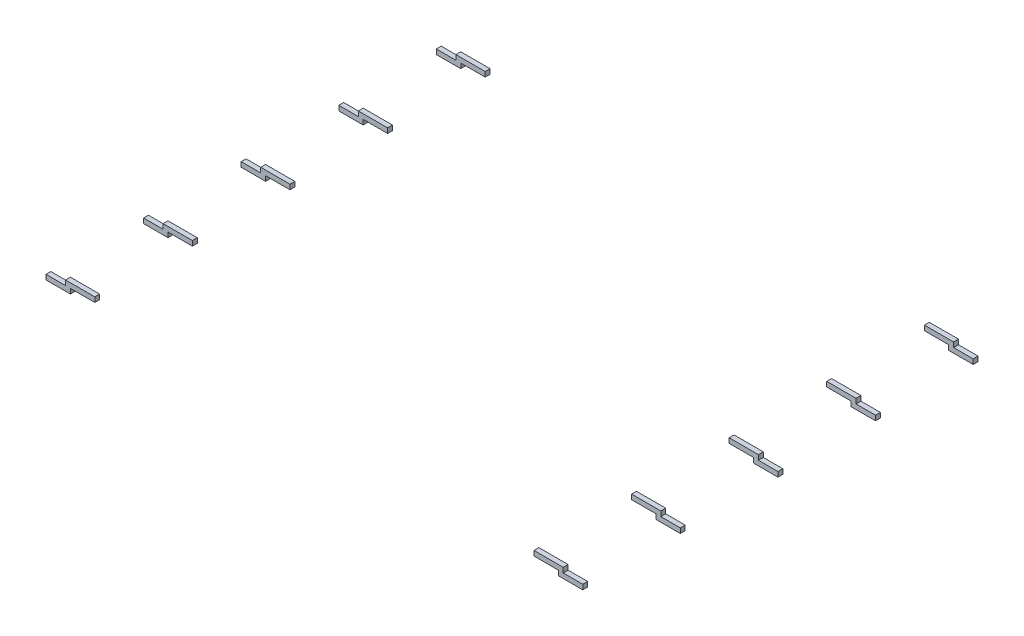
SolidWorks part; units mm, degrees
ref_plane "Front Plane" through (0, 0, 0) normal (0, 0, 1) x (1, 0, 0)
ref_plane "Top Plane" through (0, 0, 0) normal (0, 1, 0) x (1, 0, 0)
ref_plane "Right Plane" through (0, 0, 0) normal (1, 0, 0) x (0, 0, -1)
sketch "Sketch1" plane through (0, 0, 0) normal (0, 0, 1) x (1, 0, 0)
  line L0 (5.1, 0) -> (5.5, 0)
  line L1 (4.5, 0.1) -> (5.1, 0.1)
  line L2 (4.5, 0.1) -> (4.5, 0)
  line L3 (4.5, 0) -> (5, 0)
  line L4 (5.1, 0.1) -> (5.1, 0)
  line L5 (4.5, 0.1) -> (5.1, 0) construction
  line L6 (4.5, 0) -> (5.1, 0.1) construction
  line L8 (5.5, 0) -> (5.5, -0.1)
  line L9 (5.5, -0.1) -> (5, -0.1)
  line L10 (5, 0) -> (5, -0.1)
  line L11 (5.5, 0) -> (5, -0.1) construction
  line L12 (5.5, -0.1) -> (5, 0) construction
  line L13 (0, -1000) -> (0, 49000) construction
  line L14 (-5.5, -0.1) -> (-5, 0) construction
  line L15 (-5.5, 0) -> (-5, -0.1) construction
  line L16 (-4.5, 0) -> (-5.1, 0.1) construction
  line L17 (-4.5, 0.1) -> (-5.1, 0) construction
  line L34 (-5, 0) -> (-5, -0.1)
  line L35 (-5.5, -0.1) -> (-5, -0.1)
  line L36 (-5.5, 0) -> (-5.5, -0.1)
  line L37 (-5.1, 0.1) -> (-5.1, 0)
  line L38 (-4.5, 0) -> (-5, 0)
  line L39 (-4.5, 0.1) -> (-4.5, 0)
  line L40 (-4.5, 0.1) -> (-5.1, 0.1)
  line L41 (-5.1, 0) -> (-5.5, 0)
  point P0 (4.8, 0.05)
  point P5 (5.25, -0.05)
  point P10 (-4.6431, 0.025)
  point P11 (5, -0.05)
  point P13 (-3.9619, 0.075)
  point P16 (-2.5332, 0.075)
  point P17 (-0.8417, 0.075)
  point P18 (0.7237, 0.025)
  point P19 (0.978, 0.075)
  point P28 (-5.25, -0.05)
  point P29 (-4.8, 0.05)
  point P30 (5.25, 0.2103)
  point P31 (5.25, -0.2762)
  dimension "D1" = 0.1
  dimension "D2" = 0.6
  dimension "D3" = 0.5
  dimension "D4" = 0.5
  dimension "D5" = 10
extrude "Boss-Extrude1" add sketch "Sketch1" along normal mid plane 0.1
pattern_linear "LPattern1" count 5 spacing 2 along (0, 0, 1) of "Boss-Extrude1"
sketch "Sketch2" plane through (0, 0, 0) normal (0, 1, 0) x (1, 0, 0)
  line L1 (-4.8, 0.8) -> (4.8, 0.8)
  line L2 (-4.8, 0.8) -> (-4.8, -8.8)
  line L3 (-4.8, -8.8) -> (4.8, -8.8)
  line L4 (4.8, 0.8) -> (4.8, -8.8)
  line L5 (-4.8, 0.8) -> (4.8, -8.8) construction
  line L6 (-4.8, -8.8) -> (4.8, 0.8) construction
  point P0 (0, -4)
  point P5 (0.3134, 4.8742)
  point P6 (0, 0)
  point P7 (0, 0)
  point P8 (0.5034, 4.9)
  point P9 (0, 0)
  point P10 (0, 0)
  point P12 (0, 0)
  point P13 (0, 3.7247)
  point P14 (0, -3.789)
  point P15 (0, -3.664)
  dimension "D1" = 9.6
  dimension "D2" = 0.8
